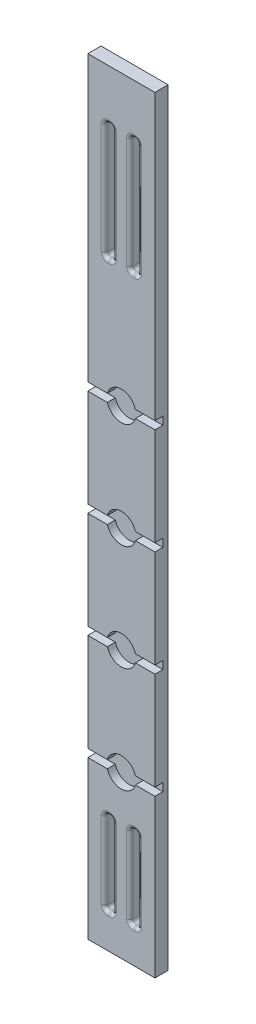
SolidWorks part; units mm, degrees
ref_plane "Front Plane" through (0, 0, 0) normal (0, 0, 1) x (1, 0, 0)
ref_plane "Top Plane" through (0, 0, 0) normal (0, 1, 0) x (1, 0, 0)
ref_plane "Right Plane" through (0, 0, 0) normal (1, 0, 0) x (0, 0, -1)
sketch "Sketch1" plane through (0, 0, 0) normal (0, 0, 1) x (1, 0, 0)
  line L1 (0, 0) -> (25.4, 0)
  line L2 (0, 0) -> (0, 290)
  line L3 (0, 290) -> (25.4, 290)
  line L4 (25.4, 0) -> (25.4, 290)
  line L5 (6.35, 270.95) -> (9.525, 270.95)
  line L6 (6.35, 270.95) -> (6.35, 226.5)
  line L7 (6.35, 226.5) -> (9.525, 226.5)
  line L8 (9.525, 270.95) -> (9.525, 226.5)
  line L9 (15.875, 270.95) -> (19.05, 270.95)
  line L10 (15.875, 270.95) -> (15.875, 226.5)
  line L11 (15.875, 226.5) -> (19.05, 226.5)
  line L12 (19.05, 270.95) -> (19.05, 226.5)
  line L13 (6.35, 44.45) -> (9.525, 44.45)
  line L14 (6.35, 44.45) -> (6.35, 12.7)
  line L15 (6.35, 12.7) -> (9.525, 12.7)
  line L16 (9.525, 44.45) -> (9.525, 12.7)
  line L17 (15.875, 44.45) -> (19.05, 44.45)
  line L18 (15.875, 44.45) -> (15.875, 12.7)
  line L19 (15.875, 12.7) -> (19.05, 12.7)
  line L20 (19.05, 44.45) -> (19.05, 12.7)
  dimension "D1" = 25.4
  dimension "D2" = 290
  dimension "D3" = 6.35
  dimension "D4" = 6.35
  dimension "D5" = 3.175
  dimension "D6" = 19.05
  dimension "D7" = 44.45
  dimension "D8" = 31.75
  dimension "D9" = 12.7
extrude "Boss-Extrude1" add sketch "Sketch1" along normal blind 5
fillet "Fillet1" radius 1.27 48 edges at (17.4625, 44.45, 5) (17.4625, 44.45, 0) (7.9375, 44.45, 5) (7.9375, 44.45, 0) (19.05, 28.575, 5) (19.05, 28.575, 0) (9.525, 28.575, 5) (9.525, 28.575, 0) (17.4625, 270.95, 5) (17.4625, 270.95, 0) (7.9375, 270.95, 5) (7.9375, 270.95, 0) (19.05, 248.725, 5) (19.05, 248.725, 0) (9.525, 248.725, 5) (9.525, 248.725, 0) (15.875, 28.575, 5) (15.875, 44.45, 2.5) (15.875, 28.575, 0) (6.35, 28.575, 5) (6.35, 44.45, 2.5) (6.35, 28.575, 0) (19.05, 12.7, 2.5) (17.4625, 12.7, 5) (15.875, 12.7, 2.5) (17.4625, 12.7, 0) (9.525, 12.7, 2.5) (7.9375, 12.7, 5) (6.35, 12.7, 2.5) (7.9375, 12.7, 0) (15.875, 248.725, 5) (15.875, 270.95, 2.5) (15.875, 248.725, 0) (6.35, 248.725, 5) (6.35, 270.95, 2.5) (6.35, 248.725, 0) (19.05, 226.5, 2.5) (17.4625, 226.5, 5) (15.875, 226.5, 2.5) (17.4625, 226.5, 0) (9.525, 226.5, 2.5) (7.9375, 226.5, 5) (6.35, 226.5, 2.5) (7.9375, 226.5, 0) (9.525, 270.95, 2.5) (9.525, 44.45, 2.5) (19.05, 44.45, 2.5) (19.05, 270.95, 2.5)
sketch "Sketch2" plane through (0, 0, 5) normal (0, 0, 1) x (1, 0, 0)
  line L0 (12.7, 290) -> (12.7, 181) construction
  line L1 (25.4, 290) -> (0, 290) construction
  line L2 (25.4, 0) -> (25.4, 290) construction
  line L3 (17.9915, 182.5) -> (25.4, 182.5)
  line L5 (17.9915, 179.5) -> (25.4, 179.5)
  line L6 (25.4, 182.5) -> (25.4, 179.5)
  line L7 (0, 290) -> (0, 0) construction
  line L8 (7.4085, 182.5) -> (0, 182.5)
  line L10 (7.4085, 179.5) -> (0, 179.5)
  line L11 (0, 182.5) -> (0, 179.5)
  line L12 (17.9915, 142.5) -> (25.4, 142.5)
  line L13 (17.9915, 139.5) -> (25.4, 139.5)
  line L14 (25.4, 142.5) -> (25.4, 139.5)
  line L15 (7.4085, 142.5) -> (0, 142.5)
  line L16 (7.4085, 139.5) -> (0, 139.5)
  line L17 (0, 142.5) -> (0, 139.5)
  line L18 (17.9915, 102.5) -> (25.4, 102.5)
  line L19 (17.9915, 99.5) -> (25.4, 99.5)
  line L20 (25.4, 102.5) -> (25.4, 99.5)
  line L21 (7.4085, 102.5) -> (0, 102.5)
  line L22 (7.4085, 99.5) -> (0, 99.5)
  line L23 (0, 102.5) -> (0, 99.5)
  line L24 (17.9915, 62.5) -> (25.4, 62.5)
  line L25 (17.9915, 59.5) -> (25.4, 59.5)
  line L26 (25.4, 62.5) -> (25.4, 59.5)
  line L27 (7.4085, 62.5) -> (0, 62.5)
  line L28 (7.4085, 59.5) -> (0, 59.5)
  line L29 (0, 62.5) -> (0, 59.5)
  arc A0 (7.4085, 179.5) -> (17.9915, 179.5) centre (12.7, 181) ccw
  arc A1 (17.9915, 182.5) -> (7.4085, 182.5) centre (12.7, 181) ccw
  arc A2 (7.4085, 139.5) -> (17.9915, 139.5) centre (12.7, 141) ccw
  arc A3 (17.9915, 142.5) -> (7.4085, 142.5) centre (12.7, 141) ccw
  arc A4 (7.4085, 99.5) -> (17.9915, 99.5) centre (12.7, 101) ccw
  arc A5 (17.9915, 102.5) -> (7.4085, 102.5) centre (12.7, 101) ccw
  arc A6 (7.4085, 59.5) -> (17.9915, 59.5) centre (12.7, 61) ccw
  arc A7 (17.9915, 62.5) -> (7.4085, 62.5) centre (12.7, 61) ccw
  point P1 (0, 181)
  point P17 (25.4, 181)
  dimension "D1" = 11
  dimension "D2" = 109
  dimension "D3" = 3
  dimension "D4" = 4
extrude "Cut-Extrude1" cut sketch "Sketch2" against normal blind 3
